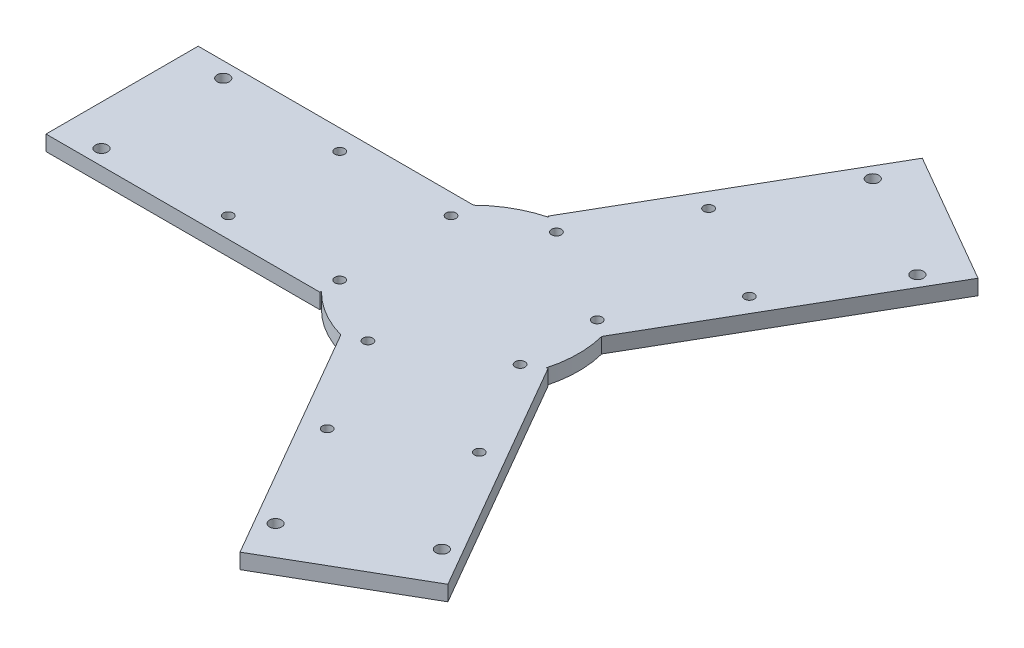
SolidWorks part; units mm, degrees
ref_plane "Plan de face" through (0, 0, 0) normal (0, 0, 1) x (1, 0, 0)
ref_plane "Plan de dessus" through (0, 0, 0) normal (0, 1, 0) x (1, 0, 0)
ref_plane "Plan de droite" through (0, 0, 0) normal (1, 0, 0) x (0, 0, -1)
sketch "Esquisse3" plane through (0, 0, 0) normal (0, 1, 0) x (1, 0, 0)
  line L0 (-150.1573, 0) -> (189.6273, 0) construction
  line L1 (-83.8395, -145.9242) -> (87.7229, 151.2306) construction
  line L2 (-78.0725, 135.2255) -> (117.7517, -203.9519) construction
  line L3 (-125, 131.2995) -> (-125, -153.5705) construction
  line L4 (-25, -25) -> (-115, -25)
  line L6 (-25, 25) -> (-24.4949, 25)
  line L7 (-115, -25) -> (-115, 25)
  line L8 (-25, -25) -> (-115, 25) construction
  line L9 (-25, 25) -> (-115, -25) construction
  line L10 (-24.4949, 25) -> (-115, 25)
  line L11 (33.8981, 8.7132) -> (79.1506, 87.0929)
  line L12 (35.8494, 112.0929) -> (79.1506, 87.0929)
  line L13 (-9.1506, 34.1506) -> (35.8494, 112.0929)
  line L14 (-9.4032, -33.7132) -> (35.8494, -112.0929)
  line L15 (79.1506, -87.0929) -> (35.8494, -112.0929)
  line L16 (34.1506, -9.1506) -> (79.1506, -87.0929)
  line L17 (-24.4949, 25) -> (-25, -25)
  line L18 (-9.1506, 34.1506) -> (33.8981, 8.7132)
  line L19 (-9.4032, -33.7132) -> (34.1506, -9.1506)
  circle A0 centre (0, 0) radius 125
  circle A1 centre (0, 0) radius 35
  circle A2 centre (0, 0) radius 125
  circle A3 centre (0, 0) radius 125
  point P9 (-70, 0)
  point P32 (0, 0)
  dimension "D1" = 250
  dimension "D4" = 70
  dimension "D2" = 120
  dimension "D3" = 120
  dimension "D5" = 10
  dimension "D6" = 50
  dimension "D7" = 90
  dimension "D8" = 3
extrude "Boss.-Extru.3" add sketch "Esquisse3" along normal blind 5 contours A1 L6 L10 L7 L4 L17 | A1 L14 L15 L16 L19 | L19 A1 L18 L17 | A1 L11 L12 L13 L18 | L18 A1
sketch "Esquisse4" plane through (0, 5, 0) normal (0, 1, 0) x (1, 0, 0)
  circle A0 centre (-101.75, 20) radius 2 construction
  circle A1 centre (-101.75, -20) radius 2 construction
  circle A2 centre (-101.75, 20) radius 2
  circle A3 centre (-101.75, -20) radius 2
  circle A4 centre (33.5545, -98.1181) radius 2 construction
  circle A5 centre (68.1955, -78.1181) radius 2 construction
  circle A6 centre (33.5545, -98.1181) radius 2
  circle A7 centre (68.1955, -78.1181) radius 2
  circle A8 centre (68.1955, 78.1181) radius 2 construction
  circle A9 centre (33.5545, 98.1181) radius 2 construction
  circle A10 centre (68.1955, 78.1181) radius 2
  circle A11 centre (33.5545, 98.1181) radius 2
  circle A12 centre (-3.2483, -30.9738) radius 1.6 construction
  circle A13 centre (15.0517, -62.6704) radius 1.6 construction
  circle A14 centre (28.4483, -12.6738) radius 1.6 construction
  circle A15 centre (46.7483, -44.3704) radius 1.6 construction
  circle A16 centre (28.4483, 12.6738) radius 1.6 construction
  circle A17 centre (46.7483, 44.3704) radius 1.6 construction
  circle A18 centre (15.0517, 62.6704) radius 1.6 construction
  circle A19 centre (-3.2483, 30.9738) radius 1.6 construction
  circle A20 centre (-25.2, 18.3) radius 1.6 construction
  circle A21 centre (-61.8, -18.3) radius 1.6 construction
  circle A22 centre (-25.2, -18.3) radius 1.6 construction
  circle A23 centre (-61.8, 18.3) radius 1.6 construction
  circle A24 centre (-3.2483, -30.9738) radius 1.6
  circle A25 centre (15.0517, -62.6704) radius 1.6
  circle A26 centre (28.4483, -12.6738) radius 1.6
  circle A27 centre (46.7483, -44.3704) radius 1.6
  circle A28 centre (28.4483, 12.6738) radius 1.6
  circle A29 centre (46.7483, 44.3704) radius 1.6
  circle A30 centre (15.0517, 62.6704) radius 1.6
  circle A31 centre (-3.2483, 30.9738) radius 1.6
  circle A32 centre (-25.2, 18.3) radius 1.6
  circle A33 centre (-61.8, -18.3) radius 1.6
  circle A34 centre (-25.2, -18.3) radius 1.6
  circle A35 centre (-61.8, 18.3) radius 1.6
extrude "Enlèv. mat.-Extru.1" cut sketch "Esquisse4" against normal through all
